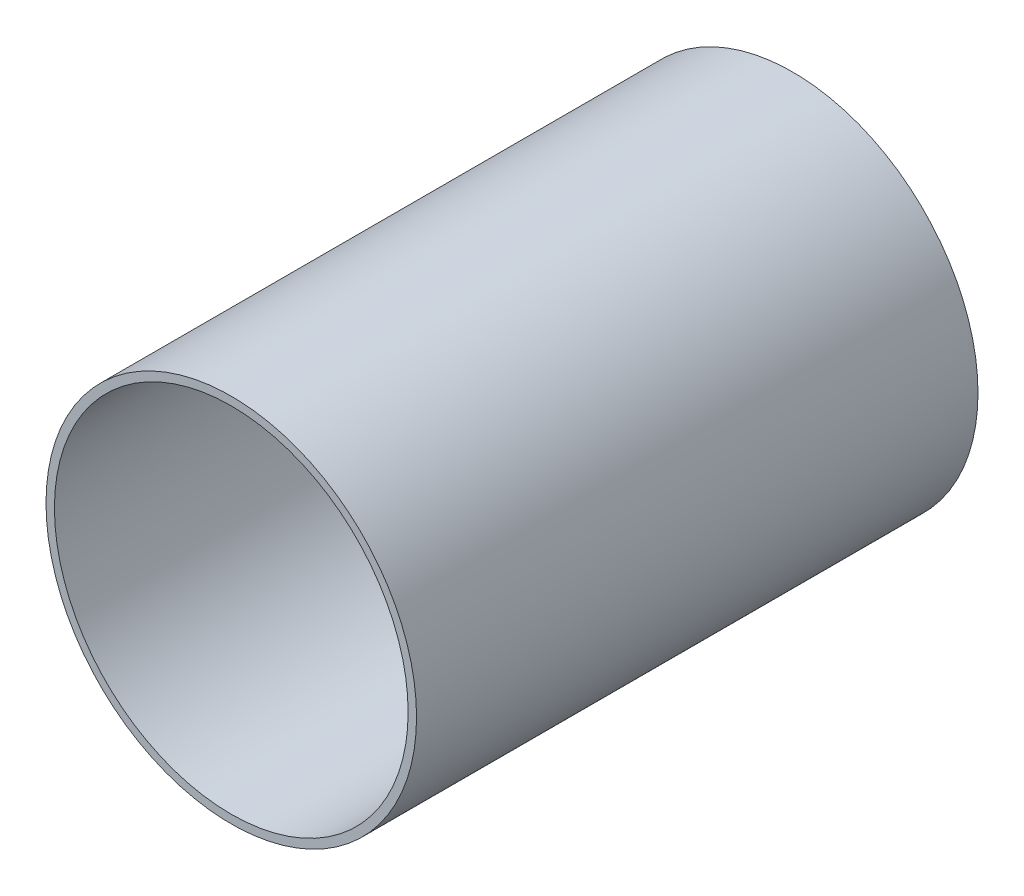
SolidWorks part; units mm, degrees
ref_plane "Plan de face" through (0, 0, 0) normal (0, 0, 1) x (1, 0, 0)
ref_plane "Plan de dessus" through (0, 0, 0) normal (0, 1, 0) x (1, 0, 0)
ref_plane "Plan de droite" through (0, 0, 0) normal (1, 0, 0) x (0, 0, -1)
sketch "Esquisse1" plane through (0, 0, 0) normal (0, 0, 1) x (1, 0, 0)
  circle A0 centre (0, 0) radius 33
  circle A1 centre (0, 0) radius 31.5
  dimension "D1" = 63
  dimension "D2" = 66
extrude "Boss.-Extru.1" add sketch "Esquisse1" along normal blind 100
